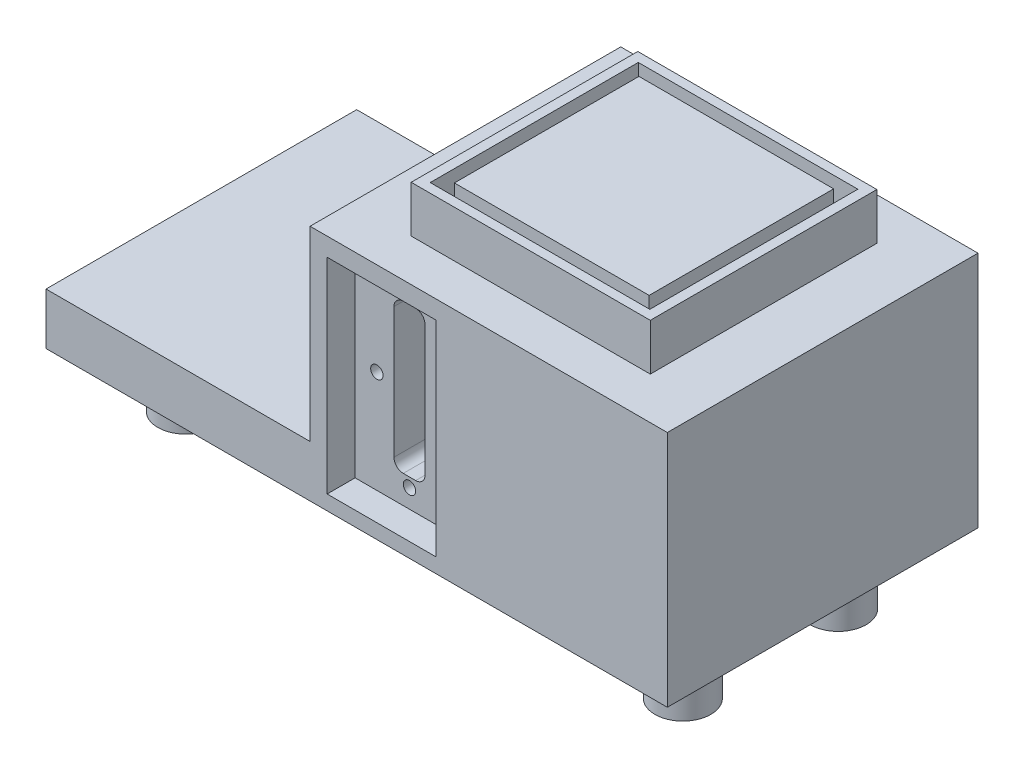
SolidWorks part; units mm, degrees
ref_plane "Front Plane" through (0, 0, 0) normal (0, 0, 1) x (1, 0, 0)
ref_plane "Top Plane" through (0, 0, 0) normal (0, 1, 0) x (1, 0, 0)
ref_plane "Right Plane" through (0, 0, 0) normal (1, 0, 0) x (0, 0, -1)
sketch "Sketch1" plane through (0, 0, 0) normal (0, 1, 0) x (1, 0, 0)
  line L7 (57.5, -50) -> (-57.5, -50)
  line L8 (57.5, -50) -> (57.5, 50)
  line L9 (57.5, 50) -> (-57.5, 50)
  line L10 (-57.5, -50) -> (-57.5, 50)
  line L11 (57.5, -50) -> (-57.5, 50) construction
  line L12 (57.5, 50) -> (-57.5, -50) construction
  point P0 (0, 0)
  dimension "D1" = 115
  dimension "D2" = 100
extrude "Boss-Extrude1" add sketch "Sketch1" along normal blind 40
sketch "Sketch8" plane through (0, 0, 0) normal (0, -1, 0) x (1, 0, 0)
  line L0 (57.5, -50) -> (-57.5, 50) construction
  line L1 (57.5, 50) -> (-57.5, -50) construction
  line L2 (57.5, 0) -> (-57.5, 0) construction
  line L3 (57.5, 50) -> (57.5, -50) construction
  line L4 (-57.5, -50) -> (-57.5, 50) construction
  line L5 (0, -50) -> (0, 50) construction
  line L6 (57.5, -50) -> (-57.5, -50) construction
  line L7 (-57.5, 50) -> (57.5, 50) construction
  circle A0 centre (0, 0) radius 7
  circle A1 centre (42.4079, -36.8764) radius 6
  circle A2 centre (42.4079, 36.8764) radius 6
  dimension "D1" = 12
  dimension "D3" = 14
  dimension "D2" = 20
extrude "Boss-Extrude4" add sketch "Sketch8" along normal blind 20
sketch "Sketch9" plane through (0, -20, 0) normal (0, -1, 0) x (1, 0, 0)
  line L0 (-57.5, 50) -> (57.5, 50) construction
  line L1 (57.5, -50) -> (-142.5, -50)
  line L2 (57.5, -50) -> (57.5, 50)
  line L3 (57.5, 50) -> (-142.5, 50)
  line L4 (-142.5, -50) -> (-142.5, 50)
  line L5 (57.5, -50) -> (-142.5, 50) construction
  line L6 (57.5, 50) -> (-142.5, -50) construction
  line L7 (57.5, 50) -> (57.5, -50) construction
  line L8 (57.5, -50) -> (-57.5, -50) construction
  point P4 (-42.5, 0)
  dimension "D1" = 200
extrude "Boss-Extrude5" add sketch "Sketch9" along normal blind 16.6
sketch "Sketch10" plane through (0, -36.6, 0) normal (0, -1, 0) x (1, 0, 0)
  line L0 (-42.5, -50) -> (-42.5, 50) construction
  line L1 (-142.5, -50) -> (57.5, -50) construction
  line L2 (57.5, 50) -> (-142.5, 50) construction
  line L3 (57.5, 0) -> (-142.5, 0) construction
  line L4 (57.5, -50) -> (57.5, 50) construction
  line L5 (-142.5, 50) -> (-142.5, -50) construction
  circle A0 centre (37.5, -25) radius 9
  circle A1 centre (-122.5, -25) radius 9
  circle A2 centre (-122.5, 25) radius 9
  circle A3 centre (37.5, 25) radius 9
  circle A4 centre (-42.5, 0) radius 10
  dimension "D1" = 18
  dimension "D4" = 20
  dimension "D2" = 20
  dimension "D3" = 25
  dimension "D5" = 20
extrude "Boss-Extrude7" add sketch "Sketch10" along normal blind 20
sketch "Sketch17" plane through (0, 0, 0) normal (0, -1, 0) x (1, 0, 0)
  line L0 (57.5, -50) -> (-57.5, -50) construction
  line L1 (-57.5, 50) -> (-42.5, 50)
  line L2 (-57.5, 50) -> (-57.5, -50)
  line L3 (-57.5, -50) -> (-42.5, -50)
  line L4 (-42.5, 50) -> (-42.5, -50)
  line L5 (-57.5, 50) -> (-42.5, -50) construction
  line L6 (-57.5, -50) -> (-42.5, 50) construction
  point P4 (-50, 0)
  dimension "D1" = 15
extrude "Boss-Extrude15" add sketch "Sketch17" along normal blind 20
sketch "Sketch15" plane through (0, -20, 0) normal (0, 1, 0) x (1, 0, 0)
  line L0 (-64.5, 0) -> (-57.5, 0) construction
  line L1 (-142.5, 50) -> (-57.5, 50) construction
  circle A0 centre (-79, 0) radius 14.5
  dimension "D1" = 29
  dimension "D2" = 50
  dimension "D3" = 7
extrude "Cut-Extrude2" cut sketch "Sketch15" against normal blind 10
sketch "Sketch21" plane through (0, -30, 0) normal (0, 1, 0) x (1, 0, 0)
  line L0 (-79, -14.4658) -> (-79, 14.4658) construction
  line L1 (-64.5342, 0) -> (-93.4658, 0) construction
  circle A0 centre (-90, 0) radius 2
  circle A1 centre (-68, 0) radius 2
  circle A2 centre (-79, 0) radius 14.4658 construction
  circle A3 centre (-79, 0) radius 6.075
  dimension "D1" = 4
  dimension "D2" = 4
  dimension "D3" = 22
  dimension "D5" = 12.15
  dimension "D4" = 11
extrude "Cut-Extrude3" cut sketch "Sketch21" against normal blind 20 contours A0 | A1 | A3
sketch "Sketch28" plane through (0, 0, 0) normal (0, -1, 0) x (1, 0, 0)
  line L0 (-42.5, 50) -> (57.5, 50) construction
  line L1 (-42.5, 50) -> (57.5, 50)
  line L2 (-42.5, 50) -> (-42.5, -50)
  line L3 (-42.5, -50) -> (57.5, -50)
  line L4 (57.5, 50) -> (57.5, -50)
  line L5 (-42.5, 50) -> (57.5, -50) construction
  line L6 (-42.5, -50) -> (57.5, 50) construction
  line L8 (-42.5, -50) -> (-42.5, 50) construction
  point P4 (7.5, 0)
extrude "Boss-Extrude16" add sketch "Sketch28" along normal blind 20
sketch "Sketch19" plane through (-57.5, 0, 0) normal (-1, 0, 0) x (0, 0, 1)
  line L0 (0, 40) -> (0, -20) construction
  line L1 (-50, 40) -> (50, 40) construction
  line L2 (50, -20) -> (-50, -20) construction
  line L3 (-27.33, -16) -> (0, -16) construction
  line L4 (-27.33, 10) -> (0, 10) construction
  circle A0 centre (-27.33, -16) radius 2
  circle A2 centre (-27.33, 10) radius 2
  circle A3 centre (27.33, -16) radius 2
  circle A4 centre (27.33, 10) radius 2
  dimension "D2" = 4
  dimension "D4" = 4
  dimension "D5" = 26
  dimension "D1" = 27.33
  dimension "D3" = 27.33
  dimension "D6" = 4
extrude "Cut-Extrude4" cut sketch "Sketch19" against normal blind 40
sketch "Sketch11" plane through (0, 40, 0) normal (0, 1, 0) x (1, 0, 0)
  line L0 (-57.5, 0) -> (57.5, 0) construction
  line L5 (-38.48, -36.4664) -> (38.48, -36.4664)
  line L6 (-38.48, -36.4664) -> (-38.48, 36.4664)
  line L11 (-38.48, 36.4664) -> (38.48, 36.4664)
  line L12 (38.48, -36.4664) -> (38.48, 36.4664)
  line L17 (-38.48, -36.4664) -> (38.48, 36.4664) construction
  line L18 (-38.48, 36.4664) -> (38.48, -36.4664) construction
  line L19 (-57.5, -50) -> (-57.5, 50) construction
  line L20 (57.5, -50) -> (57.5, 50) construction
  line L23 (-35.34, -33.4907) -> (35.34, -33.4907)
  line L24 (-35.34, -33.4907) -> (-35.34, 33.4907)
  line L25 (-35.34, 33.4907) -> (35.34, 33.4907)
  line L26 (35.34, -33.4907) -> (35.34, 33.4907)
  line L27 (-35.34, -33.4907) -> (35.34, 33.4907) construction
  line L28 (-35.34, 33.4907) -> (35.34, -33.4907) construction
  line L30 (-31.34, -29.7) -> (31.34, -29.7)
  line L31 (-31.34, -29.7) -> (-31.34, 29.7)
  line L32 (-31.34, 29.7) -> (31.34, 29.7)
  line L33 (31.34, -29.7) -> (31.34, 29.7)
  line L34 (-31.34, -29.7) -> (31.34, 29.7) construction
  line L35 (-31.34, 29.7) -> (31.34, -29.7) construction
  line L40 (-26.3933, -25.0122) -> (26.3933, 25.0122) construction
  point P0 (0, 0)
  point P6 (0, 0)
  point P7 (0, 0)
  point P11 (0, 0)
  point P15 (0, 0)
  point P16 (0, 0)
  point P21 (0, 0)
  point P26 (0, 0)
  dimension "D1" = 62.68
  dimension "D2" = 59.4
  dimension "D3" = 3.14
  dimension "D4" = 4
extrude "Boss-Extrude17" add sketch "Sketch11" along normal blind 15 contours L30 L33 L32 L31 | L5 L12 L11 L6 L26 L23 L24 L25
sketch "Sketch35" plane through (0, 40, 0) normal (0, 1, 0) x (1, 0, 0)
  line L0 (-31.34, 0) -> (-35.34, 0) construction
  line L5 (-33.34, -33.4907) -> (-33.34, 33.4907) construction
  line L6 (-35.34, 33.4907) -> (35.34, 33.4907) construction
  line L7 (-35.34, -33.4907) -> (35.34, -33.4907) construction
  line L8 (-31.34, -29.7) -> (-31.34, 29.7) construction
  line L13 (-35.34, -33.4907) -> (-35.34, 33.4907) construction
  line L14 (35.34, 0) -> (-35.34, 0) construction
  line L15 (0, -50) -> (0, 50) construction
  line L16 (-57.5, -50) -> (57.5, -50) construction
  line L17 (57.5, 50) -> (-57.5, 50) construction
  line L31 (-22.7, -30.0907) -> (-7.7, -30.0907)
  line L32 (35.34, -33.4907) -> (35.34, 33.4907) construction
  line L33 (-22.7, 33.0907) -> (-22.7, 30.0907)
  line L34 (-7.7, -33.0907) -> (-7.7, -30.0907)
  line L35 (-22.7, -33.0907) -> (-7.7, -33.0907)
  line L40 (-31.34, -29.7) -> (31.34, -29.7) construction
  line L41 (22.7, -33.0907) -> (7.7, -33.0907)
  line L42 (-22.7, 33.0907) -> (-7.7, 33.0907)
  line L43 (-7.7, 33.0907) -> (-7.7, 30.0907)
  line L44 (-22.7, 30.0907) -> (-7.7, 30.0907)
  line L53 (-22.7, -33.0907) -> (-22.7, -30.0907)
  line L55 (22.7, -33.0907) -> (22.7, -30.0907)
  line L56 (22.7, -30.0907) -> (7.7, -30.0907)
  line L57 (7.7, -33.0907) -> (7.7, -30.0907)
  line L59 (22.7, -31.5907) -> (7.7, -31.5907) construction
  line L73 (22.7, 30.0907) -> (7.7, 30.0907)
  line L74 (7.7, 33.0907) -> (7.7, 30.0907)
  line L75 (22.7, 33.0907) -> (7.7, 33.0907)
  line L76 (22.7, 33.0907) -> (22.7, 30.0907)
  line L77 (-31.84, 7.5) -> (-34.84, 7.5)
  line L78 (-31.84, -22.5) -> (-34.84, -22.5)
  line L79 (-31.84, -22.5) -> (-31.84, -7.5)
  line L80 (-31.84, -7.5) -> (-34.84, -7.5)
  line L81 (-34.84, -22.5) -> (-34.84, -7.5)
  line L82 (-33.34, -7.5) -> (-33.34, -22.5) construction
  line L83 (-31.84, -15) -> (-34.84, -15) construction
  line L84 (-34.84, 22.5) -> (-34.84, 7.5)
  line L85 (-31.84, 22.5) -> (-34.84, 22.5)
  line L86 (-31.84, 22.5) -> (-31.84, 7.5)
  line L87 (31.84, 22.5) -> (31.84, 7.5)
  line L88 (31.84, 22.5) -> (34.84, 22.5)
  line L89 (34.84, 22.5) -> (34.84, 7.5)
  line L90 (31.84, 7.5) -> (34.84, 7.5)
  line L91 (31.84, -7.5) -> (34.84, -7.5)
  line L92 (34.84, -22.5) -> (34.84, -7.5)
  line L93 (31.84, -22.5) -> (34.84, -22.5)
  line L94 (31.84, -22.5) -> (31.84, -7.5)
  point P28 (-33.34, 0)
  point P294 (-33.34, -15)
  dimension "D2" = 3
  dimension "D3" = 15
  dimension "D4" = 0.4
  dimension "D5" = 0.3907
  dimension "D6" = 7.5
  dimension "D7" = 7.7
  dimension "D9" = 15
  dimension "D12" = 3
extrude "Cut-Extrude14" cut sketch "Sketch35" against normal blind 3
sketch "Sketch36" plane through (0, 0, 50) normal (0, 0, 1) x (1, 0, 0)
  line L0 (-57.5, 40) -> (-57.5, -20) construction
  line L1 (-39.5, 25.1071) -> (-29.5, 25.1071)
  line L2 (-39.5, 25.1071) -> (-39.5, -22.8929)
  line L3 (-39.5, -22.8929) -> (-29.5, -22.8929)
  line L4 (-29.5, 25.1071) -> (-29.5, -22.8929)
  line L5 (-39.5, 25.1071) -> (-29.5, -22.8929) construction
  line L6 (-39.5, -22.8929) -> (-29.5, 25.1071) construction
  line L7 (-57.5, 40) -> (57.5, 40) construction
  point P4 (-34.5, 1.1071)
  dimension "D1" = 18
  dimension "D2" = 10
  dimension "D3" = 48
  dimension "D4" = 14.8929
extrude "Cut-Extrude15" cut sketch "Sketch36" against normal blind 32
sketch "Sketch37" plane through (-39.5, 0, 0) normal (1, 0, 0) x (0, 0, -1)
  line L7 (-29.2064, 13.25) -> (-31.0828, 10)
  line L8 (-31.0828, 10) -> (-29.2064, 6.75)
  line L9 (-29.2064, 6.75) -> (-25.4536, 6.75)
  line L10 (-25.4536, 6.75) -> (-23.5772, 10)
  line L11 (-23.5772, 10) -> (-25.4536, 13.25)
  line L12 (-25.4536, 13.25) -> (-29.2064, 13.25)
  line L13 (-29.2064, -12.75) -> (-31.0828, -16)
  line L14 (-31.0828, -16) -> (-29.2064, -19.25)
  line L15 (-29.2064, -19.25) -> (-25.4536, -19.25)
  line L16 (-25.4536, -19.25) -> (-23.5772, -16)
  line L17 (-23.5772, -16) -> (-25.4536, -12.75)
  line L18 (-25.4536, -12.75) -> (-29.2064, -12.75)
  circle A0 centre (-27.33, 10) radius 3.25 construction
  circle A1 centre (-27.33, -16) radius 3.25 construction
  dimension "D1" = 6.5
  dimension "D2" = 6.5
extrude "Cut-Extrude16" cut sketch "Sketch37" against normal blind 3
fillet "Fillet1" radius 3 7 edges at (-29.5, -22.8929, 34) (-39.5, -22.8929, 34) (-39.5, 1.1071, 18) (-29.5, 1.1071, 18) (-29.5, 25.1071, 34) (-34.5, 25.1071, 18) (-39.5, 25.1071, 34)
sketch "Sketch42" plane through (0, 0, 50) normal (0, 0, 1) x (1, 0, 0)
  line L0 (-34.5, -36.6) -> (-34.5, 40) construction
  line L1 (57.5, -36.6) -> (-142.5, -36.6) construction
  line L2 (-57.5, 40) -> (57.5, 40) construction
  line L3 (-57.5, 40) -> (-57.5, -20) construction
  line L4 (-52, 34.1071) -> (-17, 34.1071)
  line L5 (-52, 34.1071) -> (-52, -31.8929)
  line L6 (-52, -31.8929) -> (-17, -31.8929)
  line L7 (-17, 34.1071) -> (-17, -31.8929)
  line L8 (-52, 34.1071) -> (-17, -31.8929) construction
  line L9 (-52, -31.8929) -> (-17, 34.1071) construction
  line L14 (-29.5, 22.1071) -> (-29.5, -19.8929) construction
  line L15 (-52, 1.1071) -> (-17, 1.1071) construction
  point P10 (-34.5, 1.1071)
  point P13 (-34.5, 34.1071)
  point P28 (-29.5, 1.1071)
  dimension "D1" = 23
  dimension "D2" = 66
  dimension "D3" = 35
extrude "Cut-Extrude20" cut sketch "Sketch42" against normal blind 9
sketch "Sketch43" plane through (0, 0, 41) normal (0, 0, 1) x (1, 0, 0)
  line L0 (-34.5, 34.1071) -> (-34.5, -31.8929) construction
  line L1 (-52, 34.1071) -> (-17, 34.1071) construction
  line L2 (-52, 34.1071) -> (-52, -31.8929) construction
  line L3 (-52, -31.8929) -> (-17, -31.8929) construction
  line L4 (-17, 34.1071) -> (-17, -31.8929) construction
  line L5 (-52, 34.1071) -> (-17, -31.8929) construction
  line L6 (-52, -31.8929) -> (-17, 34.1071) construction
  line L7 (-52, 1.1071) -> (-17, 1.1071) construction
  circle A0 centre (-34.5, 28.1071) radius 2
  circle A1 centre (-24, 1.1071) radius 2
  circle A2 centre (-34.5, -25.8929) radius 2
  circle A3 centre (-45, 1.1071) radius 2
  point P4 (-34.5, 1.1071)
  dimension "D1" = 4
  dimension "D3" = 7
  dimension "D4" = 4
  dimension "D2" = 6
extrude "Cut-Extrude21" cut sketch "Sketch43" against normal blind 9
sketch "Sketch45" plane through (0, 0, -50) normal (0, 0, -1) x (-1, 0, 0)
  line L0 (-57.5, 40) -> (57.5, 40) construction
  line L1 (29.5, 25.11) -> (39.5, 25.11)
  line L2 (29.5, 25.11) -> (29.5, -22.89)
  line L3 (29.5, -22.89) -> (39.5, -22.89)
  line L4 (39.5, 25.11) -> (39.5, -22.89)
  line L5 (29.5, 25.11) -> (39.5, -22.89) construction
  line L6 (29.5, -22.89) -> (39.5, 25.11) construction
  line L7 (57.5, 40) -> (57.5, -20) construction
  point P4 (34.5, 1.11)
  dimension "D1" = 14.89
  dimension "D2" = 10
  dimension "D3" = 48
  dimension "D4" = 18
extrude "Cut-Extrude22" cut sketch "Sketch45" against normal blind 32
sketch "Sketch46" plane through (-39.5, 0, 0) normal (1, 0, 0) x (0, 0, -1)
  line L1 (29.2064, 13.25) -> (25.4536, 13.25)
  line L2 (25.4536, 13.25) -> (23.5772, 10)
  line L3 (23.5772, 10) -> (25.4536, 6.75)
  line L4 (25.4536, 6.75) -> (29.2064, 6.75)
  line L5 (29.2064, 6.75) -> (31.0828, 10)
  line L6 (31.0828, 10) -> (29.2064, 13.25)
  line L7 (25.4536, -12.75) -> (23.5772, -16)
  line L8 (23.5772, -16) -> (25.4536, -19.25)
  line L9 (25.4536, -19.25) -> (29.2064, -19.25)
  line L10 (29.2064, -19.25) -> (31.0828, -16)
  line L11 (31.0828, -16) -> (29.2064, -12.75)
  line L12 (29.2064, -12.75) -> (25.4536, -12.75)
  circle A0 centre (27.33, 10) radius 3.25 construction
  circle A1 centre (27.33, -16) radius 3.25 construction
  dimension "D1" = 6.5
  dimension "D2" = 6.5
extrude "Cut-Extrude23" cut sketch "Sketch46" against normal blind 3
fillet "Fillet2" radius 3 8 edges at (-34.5, -22.89, -18) (-29.5, -22.89, -34) (-39.5, -22.89, -34) (-39.5, 1.11, -18) (-29.5, 1.11, -18) (-29.5, 25.11, -34) (-34.5, 25.11, -18) (-39.5, 25.11, -34)
sketch "Sketch47" plane through (0, 0, -50) normal (0, 0, -1) x (-1, 0, 0)
  line L0 (34.5, 40) -> (34.5, -37.78) construction
  line L1 (17, 34.11) -> (52, 34.11)
  line L2 (17, 34.11) -> (17, -31.89)
  line L3 (17, -31.89) -> (52, -31.89)
  line L4 (52, 34.11) -> (52, -31.89)
  line L5 (17, 34.11) -> (52, -31.89) construction
  line L6 (17, -31.89) -> (52, 34.11) construction
  line L7 (-57.5, 40) -> (57.5, 40) construction
  line L8 (57.5, 40) -> (57.5, -20) construction
  line L9 (57.5, 1.11) -> (-57.5, 1.11) construction
  line L10 (-57.5, 40) -> (-57.5, -36.6) construction
  line L11 (142.5, -36.6) -> (-57.5, -36.6) construction
  point P4 (34.5, 1.11)
  point P12 (34.5, 1.11)
  dimension "D1" = 23
  dimension "D2" = 37.71
  dimension "D3" = 35
  dimension "D4" = 66
extrude "Cut-Extrude24" cut sketch "Sketch47" against normal blind 9
sketch "Sketch48" plane through (0, 0, -41) normal (0, 0, -1) x (-1, 0, 0)
  line L0 (34.5, 34.11) -> (34.5, -31.89) construction
  line L1 (52, 34.11) -> (17, 34.11) construction
  line L2 (17, -31.89) -> (52, -31.89) construction
  line L3 (17, 1.11) -> (52, 1.11) construction
  line L4 (17, 34.11) -> (17, -31.89) construction
  line L5 (52, -31.89) -> (52, 34.11) construction
  line L6 (52, -31.89) -> (52, 34.11) construction
  circle A0 centre (34.5, 28.11) radius 2
  circle A1 centre (45, 1.11) radius 2
  circle A2 centre (24, 1.11) radius 2
  circle A3 centre (34.5, -25.89) radius 2
  dimension "D1" = 4
  dimension "D3" = 4
  dimension "D2" = 6
  dimension "D4" = 7
extrude "Cut-Extrude25" cut sketch "Sketch48" against normal blind 9
